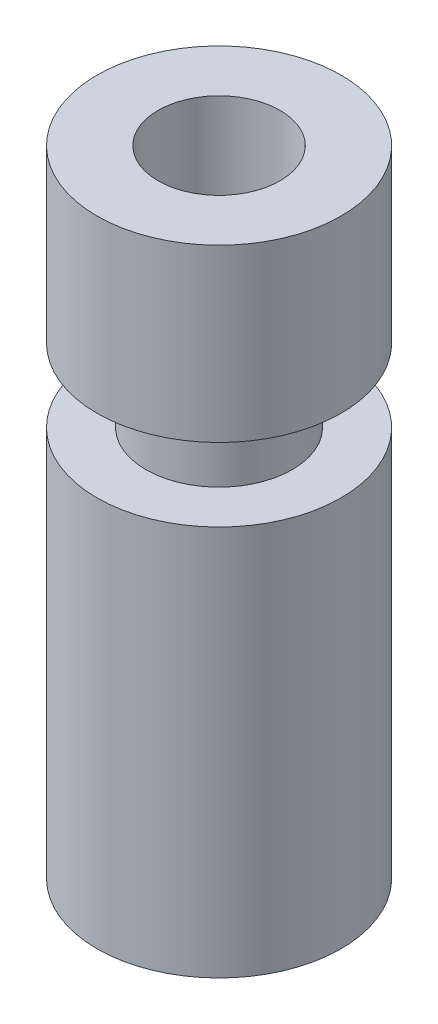
SolidWorks part; units mm, degrees
material "Stainless Steel (ferritic)"
ref_plane "Front Plane" through (0, 0, 0) normal (0, 0, 1) x (1, 0, 0)
ref_plane "Top Plane" through (0, 0, 0) normal (0, 1, 0) x (1, 0, 0)
ref_plane "Right Plane" through (0, 0, 0) normal (1, 0, 0) x (0, 0, -1)
sketch "Sketch1" plane through (0, 0, 0) normal (0, 1, 0) x (1, 0, 0)
  circle A0 centre (0, 0) radius 2.5
  dimension "D1" = 5
extrude "Boss-Extrude1" add sketch "Sketch1" along normal blind 8
sketch "Sketch2" plane through (0, 8, 0) normal (0, 1, 0) x (1, 0, 0)
  circle A0 centre (0, 0) radius 1.5
  dimension "D1" = 3
extrude "Boss-Extrude2" add sketch "Sketch2" along normal blind 1.5
sketch "Sketch3" plane through (0, 9.5, 0) normal (0, 1, 0) x (1, 0, 0)
  circle A0 centre (0, 0) radius 2.5
  dimension "D1" = 5
extrude "Boss-Extrude3" add sketch "Sketch3" along normal blind 3.5
sketch "Sketch4" plane through (0, 13, 0) normal (0, 1, 0) x (1, 0, 0)
  circle A0 centre (0, 0) radius 1.25
  dimension "D1" = 2.5
extrude "Cut-Extrude1" cut sketch "Sketch4" against normal blind 2
